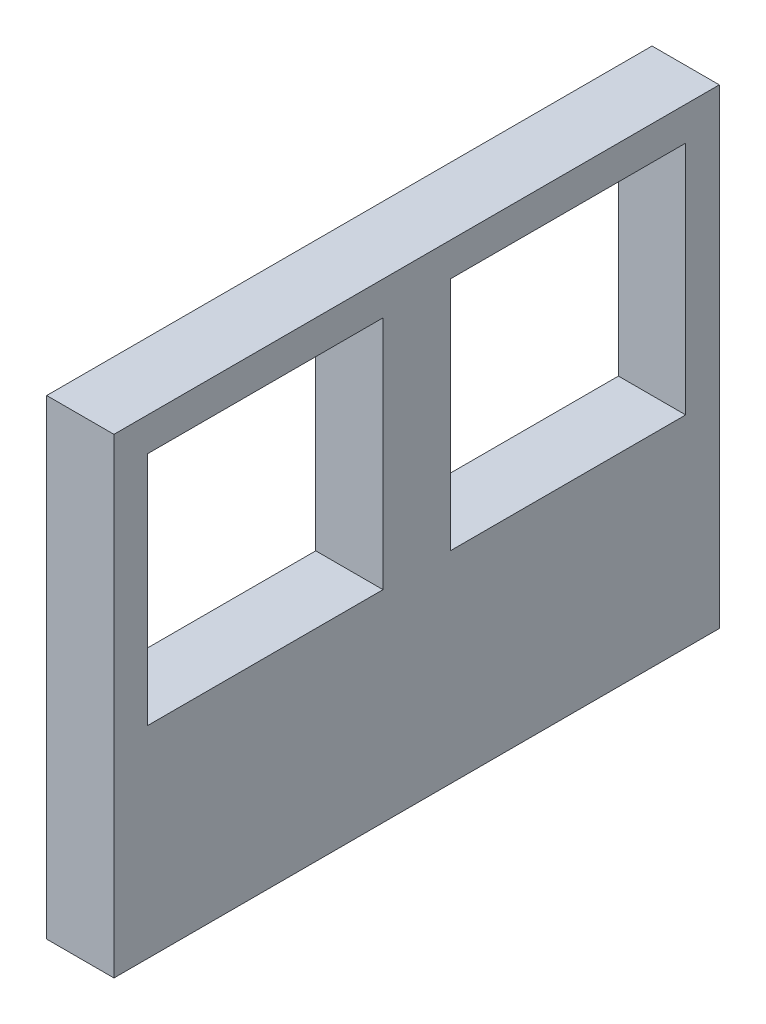
SolidWorks part; units mm, degrees
material "Сосна"
ref_plane "Спереди" through (0, 0, 0) normal (0, 0, 1) x (1, 0, 0)
ref_plane "Сверху" through (0, 0, 0) normal (0, 1, 0) x (1, 0, 0)
ref_plane "Справа" through (0, 0, 0) normal (1, 0, 0) x (0, 0, -1)
sketch3d "Трехмерный эскиз1"
  line L10 (0, -39.5292, -14.7576) -> (0, -39.5292, 21.2424)
  line L11 (0, -39.5292, -14.7576) -> (0, -11.5292, -14.7576)
  line L16 (0, -11.5292, -14.7576) -> (0, -11.5292, 21.2424)
  line L17 (0, -39.5292, 21.2424) -> (0, -11.5292, 21.2424)
  line L22 (0, -27.5292, 19.2424) -> (0, -13.5292, 19.2424)
  line L23 (0, -13.5292, 5.2424) -> (0, -13.5292, 19.2424)
  line L28 (0, -27.5292, 5.2424) -> (0, -13.5292, 5.2424)
  line L29 (0, -27.5292, 5.2424) -> (0, -27.5292, 19.2424)
  line L34 (0, -27.5292, -12.7576) -> (0, -27.5292, 1.2424)
  line L35 (0, -27.5292, 1.2424) -> (0, -13.5292, 1.2424)
  line L41 (0, -27.5292, -12.7576) -> (0, -13.5292, -12.7576)
  line L42 (0, -13.5292, -12.7576) -> (0, -13.5292, 1.2424)
  point P114 (-83.3137, -1.0149, -16.6463)
  point P263 (-83.8457, 0, -14.1783)
  point P264 (-83.8457, 0, -14.1783)
  point P265 (-83.8457, 0, -14.1783)
  point P267 (-80.8457, 0, 24.8217)
  dimension "D2" = 14
  dimension "D3" = 14
  dimension "D4" = 14
  dimension "D5" = 14
  dimension "D106" = 4
  dimension "D104" = 36
  dimension "D105" = 28
  dimension "D107" = 2
  dimension "D108" = 2
  dimension "D109" = 2
  dimension "D110" = 2
extrude "Бобышка-Вытянуть1" add sketch "Трехмерный эскиз1" along direction (1, 0, 0) on the side of the normal blind 4
